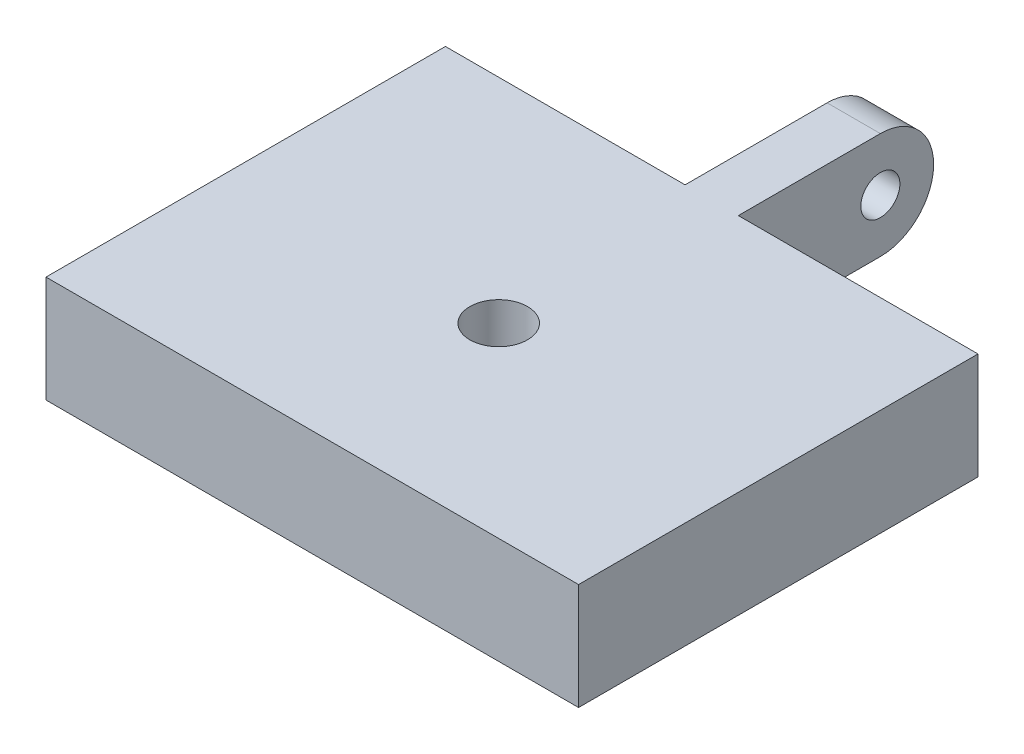
SolidWorks part; units mm, degrees
ref_plane "Front Plane" through (0, 0, 0) normal (0, 0, 1) x (1, 0, 0)
ref_plane "Top Plane" through (0, 0, 0) normal (0, 1, 0) x (1, 0, 0)
ref_plane "Right Plane" through (0, 0, 0) normal (1, 0, 0) x (0, 0, -1)
sketch "Croquis_lengueta_buje" plane through (0, 0, 0) normal (1, 0, 0) x (0, 0, -1)
  circle A0 centre (0, 0) radius 6
  dimension "D1" = 12
extrude "Lengueta_buje" add sketch "Croquis_lengueta_buje" along normal mid plane 6
sketch "Croquis_lengueta" plane through (0, 0, 0) normal (1, 0, 0) x (0, 0, -1)
  line L1 (-18, -6) -> (0, -6)
  line L2 (-18, -6) -> (-18, 6)
  line L3 (-18, 6) -> (0, 6)
  line L4 (0, -6) -> (0, 6)
  line L5 (-18, -6) -> (0, 6) construction
  line L6 (-18, 6) -> (0, -6) construction
  circle A0 centre (0, 0) radius 6 construction
  point P0 (-9, 0)
  dimension "D1" = 18
  dimension "D2" = 12
extrude "Lengueta" add sketch "Croquis_lengueta" along normal mid plane 6
ref_plane "Plano_Top Plane_-6" through (0, -6, 0) normal (0, 1, 0) x (1, 0, 0)
sketch "Croquis_ceja" plane through (0, -6, 0) normal (0, 1, 0) x (1, 0, 0)
  line L1 (-30, -61) -> (30, -61)
  line L2 (-30, -61) -> (-30, -16)
  line L3 (-30, -16) -> (30, -16)
  line L4 (30, -61) -> (30, -16)
  line L5 (-30, -61) -> (30, -16) construction
  line L6 (-30, -16) -> (30, -61) construction
  dimension "D1" = 60
  dimension "D2" = 45
extrude "Ceja_monitor" add sketch "Croquis_ceja" along normal blind 12
sketch "Croquis_rosca" plane through (0, 0, 0) normal (0, 1, 0) x (1, 0, 0)
  circle A0 centre (0, -40) radius 3.25
  dimension "D1" = 6.5
extrude "Agujero_tripode_1_4" cut sketch "Croquis_rosca" along normal through all and the other way through all
sketch "Croquis_eje" plane through (0, 0, 0) normal (1, 0, 0) x (0, 0, -1)
  circle A0 centre (0, 0) radius 2.2
  dimension "D1" = 4.4
extrude "Eje_M4" cut sketch "Croquis_eje" along normal through all and the other way through all
